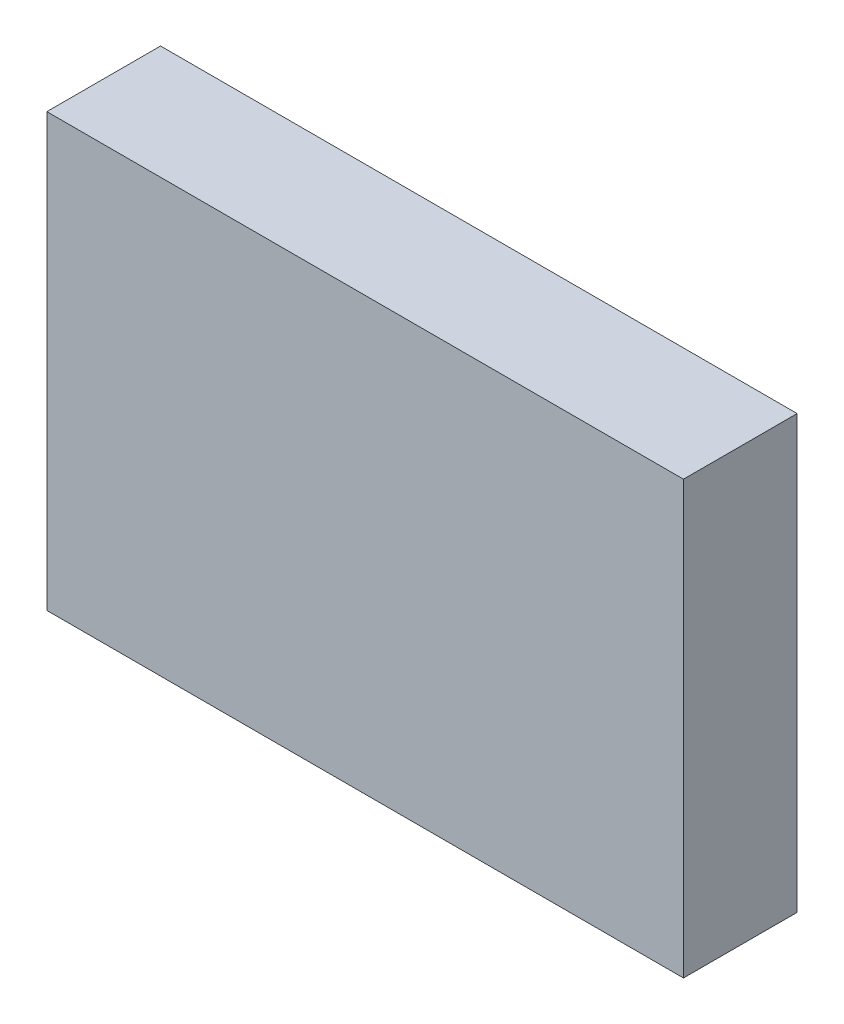
SolidWorks part; units mm, degrees
ref_plane "前视基准面" through (0, 0, 0) normal (0, 0, 1) x (1, 0, 0)
ref_plane "上视基准面" through (0, 0, 0) normal (0, 1, 0) x (1, 0, 0)
ref_plane "右视基准面" through (0, 0, 0) normal (1, 0, 0) x (0, 0, -1)
other "Configuration Table"
sketch "草图1" plane through (0, 0, 0) normal (0, 0, 1) x (1, 0, 0)
  line L1 (-70, -47.5) -> (70, -47.5)
  line L2 (-70, -47.5) -> (-70, 47.5)
  line L3 (-70, 47.5) -> (70, 47.5)
  line L4 (70, -47.5) -> (70, 47.5)
  line L5 (-70, -47.5) -> (70, 47.5) construction
  line L6 (-70, 47.5) -> (70, -47.5) construction
  point P0 (0, 0)
extrude "凸台-拉伸1" add sketch "草图1" along normal blind 25
